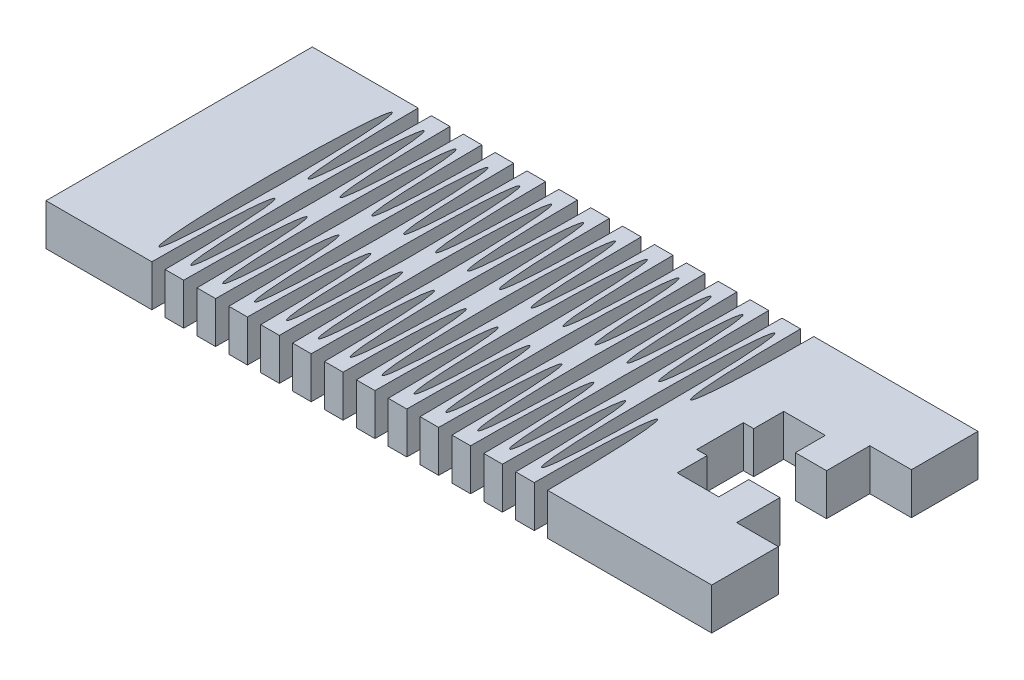
SolidWorks part; units mm, degrees
ref_plane "前视基准面" through (0, 0, 0) normal (0, 0, 1) x (1, 0, 0)
ref_plane "上视基准面" through (0, 0, 0) normal (0, 1, 0) x (1, 0, 0)
ref_plane "右视基准面" through (0, 0, 0) normal (1, 0, 0) x (0, 0, -1)
sketch "Sketch1" plane through (0, 0, 0) normal (0, 1, 0) x (1, 0, 0)
  line L1 (0, 0) -> (38.1, 0)
  line L2 (0, 0) -> (0, -20.32)
  line L3 (0, -20.32) -> (38.1, -20.32)
  line L4 (38.1, 0) -> (38.1, -20.32)
  dimension "D1" = 20.32
  dimension "D2" = 38.1
extrude "Boss-Extrude1" add sketch "Sketch1" along normal blind 3.175
sketch "Sketch4" plane through (0, 3.175, 0) normal (0, 1, 0) x (1, 0, 0)
  line L0 (38.1, -20.32) -> (38.1, 0) construction
  line L1 (38.1, -5.08) -> (34.925, -5.08)
  line L2 (38.1, -5.08) -> (38.1, -15.24)
  line L3 (38.1, -15.24) -> (34.925, -15.24)
  line L4 (34.925, -5.08) -> (34.925, -15.24)
  line L5 (38.1, 0) -> (0, 0) construction
  line L6 (0, -20.32) -> (38.1, -20.32) construction
  line L7 (34.925, -8.382) -> (28.575, -8.382)
  line L8 (34.925, -8.382) -> (34.925, -11.938)
  line L9 (34.925, -11.938) -> (28.575, -11.938)
  line L10 (28.575, -8.382) -> (28.575, -11.938)
  line M3 (38.1, -20.32) -> (38.1, 0)
  dimension "D1" = 3.175
  dimension "D2" = 5.08
  dimension "D3" = 6.35
  dimension "D4" = 3.556
  dimension "D5" = 5.08
  dimension "D6" = 3.302
extrude "Cut-Extrude1" cut sketch "Sketch4" against normal blind 3.175 contours L7 L10 L9 L4 | L1 L4 L3 M3
sketch "Sketch5" plane through (0, 3.175, 0) normal (0, 1, 0) x (1, 0, 0)
  line L0 (28.575, -8.382) -> (28.575, -11.938) construction
  line L1 (29.3688, -14.224) -> (32.5438, -14.224)
  line L2 (29.3688, -14.224) -> (29.3688, -6.096)
  line L3 (29.3688, -6.096) -> (32.5438, -6.096)
  line L4 (32.5438, -14.224) -> (32.5438, -6.096)
  line L6 (34.925, -8.382) -> (28.575, -8.382) construction
  dimension "D1" = 3.175
  dimension "D2" = 0.7937
  dimension "D3" = 8.128
  dimension "D4" = 2.286
extrude "Cut-Extrude2" cut sketch "Sketch5" against normal blind 3.175
sketch "Sketch6" plane through (0, 3.175, 0) normal (0, 1, 0) x (1, 0, 0)
  line L1 (0, 0) -> (-12.7, 0)
  line L2 (0, 0) -> (0, -20.32)
  line L3 (0, -20.32) -> (-12.7, -20.32)
  line L4 (-12.7, 0) -> (-12.7, -20.32)
  dimension "D1" = 20.32
  dimension "D2" = 12.7
extrude "Boss-Extrude2" add sketch "Sketch6" against normal blind 3.175
sketch "Sketch11" plane through (0, 3.175, 0) normal (0, 1, 0) x (1, 0, 0)
  line L0 (38.1, 0) -> (-12.7, 0) construction
  line L1 (28.575, -8.382) -> (28.575, -11.938) construction
  line L2 (-12.7, -20.32) -> (38.1, -20.32) construction
  ellipse E0 centre (25.067, 0) end of major axis (25.067, -8.89) minor radius 0.508
  ellipse E1 centre (25.067, -20.32) end of major axis (25.067, -11.43) minor radius 0.508
  dimension "D1" = 3
  dimension "D2" = 1.016
  dimension "D3" = 8.89
  dimension "D4" = 1.016
  dimension "D5" = 8.89
  dimension "D6" = 3.508
extrude "Cut-Extrude12" cut sketch "Sketch11" against normal blind 4
sketch "Sketch12" plane through (0, 3.175, 0) normal (0, 1, 0) x (1, 0, 0)
  ellipse E0 centre (23.851, -10.16) end of major axis (23.851, -1.27) minor radius 0.508
  dimension "D1" = 1.016
  dimension "D2" = 17.78
  dimension "D3" = 0.2
extrude "Cut-Extrude13" cut sketch "Sketch12" against normal blind 4
sketch "Sketch13" plane through (0, 3.175, 0) normal (0, 1, 0) x (1, 0, 0)
  line L0 (24.559, 0) -> (-12.7, 0) construction
  line L1 (-12.7, -20.32) -> (24.559, -20.32) construction
  ellipse E0 centre (22.635, 0) end of major axis (22.635, -8.89) minor radius 0.508
  ellipse E1 centre (22.635, -20.32) end of major axis (22.635, -29.21) minor radius 0.508
  ellipse E2 centre (21.419, -10.16) end of major axis (21.419, -1.27) minor radius 0.508
  ellipse E3 centre (20.203, 0) end of major axis (20.203, -8.89) minor radius 0.508
  ellipse E4 centre (20.203, -20.32) end of major axis (20.203, -29.21) minor radius 0.508
  ellipse E5 centre (18.987, -10.16) end of major axis (18.987, -19.05) minor radius 0.508
  ellipse E6 centre (17.771, 0) end of major axis (17.771, -8.89) minor radius 0.508
  ellipse E7 centre (17.771, -20.32) end of major axis (17.771, -29.21) minor radius 0.508
  ellipse E8 centre (16.555, -10.16) end of major axis (16.555, -1.27) minor radius 0.508
  ellipse E9 centre (15.339, 0) end of major axis (15.339, -8.89) minor radius 0.508
  ellipse E10 centre (15.339, -20.32) end of major axis (15.339, -29.21) minor radius 0.508
  ellipse E11 centre (14.123, -10.16) end of major axis (14.123, -1.27) minor radius 0.508
  ellipse E12 centre (12.907, 0) end of major axis (12.907, -8.89) minor radius 0.508
  ellipse E13 centre (12.907, -20.32) end of major axis (12.907, -29.21) minor radius 0.508
  ellipse E14 centre (11.691, -10.16) end of major axis (11.691, -19.05) minor radius 0.508
  ellipse E15 centre (10.475, 0) end of major axis (10.475, -8.89) minor radius 0.508
  ellipse E16 centre (10.475, -20.32) end of major axis (10.475, -11.43) minor radius 0.508
  ellipse E17 centre (9.259, -10.16) end of major axis (9.259, -1.27) minor radius 0.508
  ellipse E18 centre (8.043, 0) end of major axis (8.043, -8.89) minor radius 0.508
  ellipse E19 centre (8.043, -20.32) end of major axis (8.043, -29.21) minor radius 0.508
  ellipse E20 centre (6.827, -10.16) end of major axis (6.827, -19.05) minor radius 0.508
  ellipse E21 centre (5.611, 0) end of major axis (5.611, -8.89) minor radius 0.508
  ellipse E22 centre (5.611, -20.32) end of major axis (5.611, -29.21) minor radius 0.508
  ellipse E23 centre (4.395, -10.16) end of major axis (4.395, -19.05) minor radius 0.508
  ellipse E24 centre (3.179, 0) end of major axis (3.179, -8.89) minor radius 0.508
  ellipse E25 centre (3.179, -20.32) end of major axis (3.179, -29.21) minor radius 0.508
  ellipse E26 centre (1.963, -10.16) end of major axis (1.963, -1.27) minor radius 0.508
  ellipse E27 centre (0.747, 0) end of major axis (0.747, -8.89) minor radius 0.508
  ellipse E28 centre (0.747, -20.32) end of major axis (0.747, -29.21) minor radius 0.508
  ellipse E29 centre (-0.469, -10.16) end of major axis (-0.469, -19.05) minor radius 0.508
  ellipse E30 centre (-1.685, 0) end of major axis (-1.685, -8.89) minor radius 0.508
  ellipse E31 centre (-1.685, -20.32) end of major axis (-1.685, -29.21) minor radius 0.508
  ellipse E32 centre (-2.901, -10.16) end of major axis (-2.901, -19.05) minor radius 0.508
  ellipse E33 centre (-4.117, 0) end of major axis (-4.117, -8.89) minor radius 0.508
  ellipse E34 centre (-4.117, -20.32) end of major axis (-4.117, -29.21) minor radius 0.508
  ellipse E35 centre (-5.333, -10.16) end of major axis (-5.333, -19.05) minor radius 0.508
  dimension "D1" = 1.016
  dimension "D2" = 8.89
  dimension "D3" = 1.416
  dimension "D4" = 17.78
  dimension "D5" = 1.016
  dimension "D6" = 1.016
  dimension "D7" = 17.78
  dimension "D8" = 0.2
  dimension "D9" = 1.016
  dimension "D10" = 8.89
  dimension "D11" = 1.416
  dimension "D12" = 0
  dimension "D13" = 2.432
  dimension "D14" = 2.432
  dimension "D15" = 0
  dimension "D16" = 1.016
  dimension "D17" = 8.89
  dimension "D18" = 17.78
  dimension "D19" = 1.016
  dimension "D20" = 1.016
  dimension "D21" = 17.78
  dimension "D22" = 0.2
  dimension "D23" = 1.016
  dimension "D24" = 8.89
  dimension "D25" = 1.416
  dimension "D26" = 2.432
  dimension "D27" = 2.432
  dimension "D28" = 0
  dimension "D29" = 2.432
  dimension "D30" = 0
  dimension "D31" = 0
  dimension "D32" = 2.432
  dimension "D33" = 0
  dimension "D34" = 1.016
  dimension "D35" = 8.89
  dimension "D36" = 17.78
  dimension "D37" = 1.016
  dimension "D38" = 1.016
  dimension "D39" = 17.78
  dimension "D40" = 0.2
  dimension "D41" = 1.016
  dimension "D42" = 8.89
  dimension "D43" = 1.416
  dimension "D44" = 2.432
  dimension "D45" = 2.432
  dimension "D46" = 0
  dimension "D47" = 1.016
  dimension "D48" = 8.89
  dimension "D49" = 17.78
  dimension "D50" = 1.016
  dimension "D51" = 1.016
  dimension "D52" = 17.78
  dimension "D53" = 0.2
  dimension "D54" = 1.016
  dimension "D55" = 8.89
  dimension "D56" = 1.416
  dimension "D57" = 2.432
  dimension "D58" = 2.432
  dimension "D59" = 0
  dimension "D60" = 2.432
  dimension "D61" = 0
  dimension "D62" = 0
  dimension "D63" = 2.432
  dimension "D64" = 0
  dimension "D65" = 0
  dimension "D66" = 2.432
  dimension "D67" = 1.216
  dimension "D68" = 1.016
  dimension "D69" = 8.89
  dimension "D70" = 17.78
  dimension "D71" = 1.016
  dimension "D72" = 1.016
  dimension "D73" = 17.78
  dimension "D74" = 0.2
  dimension "D75" = 1.016
  dimension "D76" = 8.89
  dimension "D77" = 1.416
  dimension "D78" = 2.432
  dimension "D79" = 2.432
  dimension "D80" = 0
  dimension "D81" = 1.016
  dimension "D82" = 8.89
  dimension "D83" = 17.78
  dimension "D84" = 1.016
  dimension "D85" = 1.016
  dimension "D86" = 17.78
  dimension "D87" = 0.2
  dimension "D88" = 1.016
  dimension "D89" = 8.89
  dimension "D90" = 1.416
  dimension "D91" = 2.432
  dimension "D92" = 2.432
  dimension "D93" = 0
  dimension "D94" = 2.432
  dimension "D95" = 0
  dimension "D96" = 0
  dimension "D97" = 2.432
  dimension "D98" = 0
  dimension "D99" = 1.27
  dimension "D100" = 0.708
  dimension "D101" = 0
  dimension "D132" = 1.216
extrude "Cut-Extrude15" cut sketch "Sketch13" against normal blind 4
